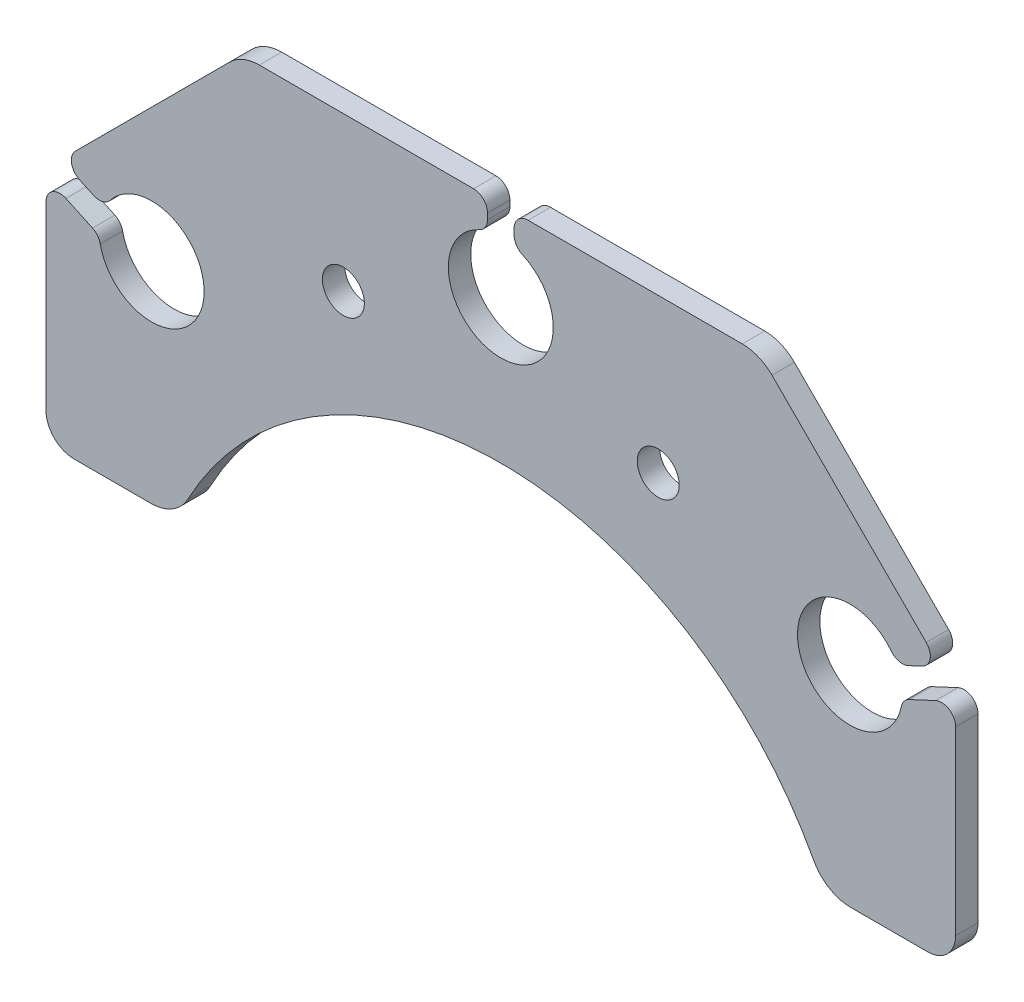
SolidWorks part; units mm, degrees
ref_plane "Ön Düzlem" through (0, 0, 0) normal (0, 0, 1) x (1, 0, 0)
ref_plane "Üst Düzlem" through (0, 0, 0) normal (0, 1, 0) x (1, 0, 0)
ref_plane "Sağ Düzlem" through (0, 0, 0) normal (1, 0, 0) x (0, 0, -1)
sketch "Çizim1" plane through (0, 0, 0) normal (0, 0, 1) x (1, 0, 0)
  line L0 (51.8787, -0.8787) -> (62.9014, -11.9014)
  line L1 (15.2426, 0) -> (30.55, 0)
  line L2 (0, -16.0697) -> (0, -29)
  line L3 (2, -31) -> (7.4942, -31)
  line L4 (65, -16.0697) -> (65, -29)
  line L5 (2.0986, -11.9014) -> (13.1213, -0.8787)
  line L6 (15.8302, -16) -> (49.1698, -16) construction
  line L7 (31.55, -1.4187) -> (31.55, -1)
  line L8 (33.45, -1.4187) -> (33.45, -1)
  line L9 (34.45, 0) -> (49.7574, 0)
  line L10 (57.5058, -31) -> (63, -31)
  line L11 (3.3844, -13.9818) -> (2.3831, -13.5148)
  line L12 (3.3194, -16.0479) -> (1.4226, -15.1634)
  line L13 (32.5, -41.343) -> (32.5, -25.2413) construction
  line L14 (61.6156, -13.9818) -> (62.6169, -13.5148)
  line L15 (61.6806, -16.0479) -> (63.5774, -15.1634)
  arc A0 (10.141, -29.4123) -> (54.859, -29.4123) centre (32.5, -41.343) cw
  arc A1 (30.9605, -2.3306) -> (34.0395, -2.3306) centre (32.5, -5.75) ccw
  arc A2 (3.8764, -16.7533) -> (4.595, -13.6912) centre (7.55, -16) ccw
  arc A3 (60.405, -13.6912) -> (61.1236, -16.7533) centre (57.45, -16) ccw
  circle A4 centre (21.25, -11) radius 1.5
  circle A5 centre (43.75, -11) radius 1.5
  arc A6 (33.45, -1.4187) -> (34.0395, -2.3306) centre (34.45, -1.4187) ccw
  arc A7 (31.55, -1.4187) -> (30.9605, -2.3306) centre (30.55, -1.4187) cw
  arc A8 (33.45, -1) -> (34.45, 0) centre (34.45, -1) cw
  arc A9 (31.55, -1) -> (30.55, 0) centre (30.55, -1) ccw
  arc A10 (61.6156, -13.9818) -> (60.405, -13.6912) centre (61.1929, -13.0755) cw
  arc A11 (61.6806, -16.0479) -> (61.1236, -16.7533) centre (62.1032, -16.9542) ccw
  arc A12 (63.5774, -15.1634) -> (65, -16.0697) centre (64, -16.0697) cw
  arc A13 (62.6169, -13.5148) -> (62.9014, -11.9014) centre (62.1943, -12.6085) ccw
  arc A14 (3.3844, -13.9818) -> (4.595, -13.6912) centre (3.8071, -13.0755) ccw
  arc A15 (3.3194, -16.0479) -> (3.8764, -16.7533) centre (2.8968, -16.9542) cw
  arc A16 (2.3831, -13.5148) -> (2.0986, -11.9014) centre (2.8057, -12.6085) cw
  arc A17 (1.4226, -15.1634) -> (0, -16.0697) centre (1, -16.0697) ccw
  arc A18 (51.8787, -0.8787) -> (49.7574, 0) centre (49.7574, -3) ccw
  arc A19 (13.1213, -0.8787) -> (15.2426, 0) centre (15.2426, -3) cw
  arc A20 (54.859, -29.4123) -> (57.5058, -31) centre (57.5058, -28) ccw
  arc A21 (10.141, -29.4123) -> (7.4942, -31) centre (7.4942, -28) cw
  arc A22 (63, -31) -> (65, -29) centre (63, -29) ccw
  arc A23 (0, -29) -> (2, -31) centre (2, -29) ccw
  point P0 (0, 0)
  point P3 (65, 0)
  point P37 (33.45, 0)
  point P42 (60.8191, -14.3532)
  point P45 (61.1898, -16.2767)
  point P50 (63.9113, -12.9113)
  point P53 (4.1809, -14.3532)
  point P57 (3.8102, -16.2767)
  point P60 (1.0887, -12.9113)
  point P63 (0, -14.5)
  point P66 (51, 0)
  point P69 (14, 0)
  point P72 (55.6363, -31)
  point P75 (9.3637, -31)
  point P80 (0, -31)
  dimension "D7" = 7.5
  dimension "D8" = 3
  dimension "D9" = 11
  dimension "D10" = 22.5
  dimension "D11" = 32.5
  dimension "D12" = 5.75
  dimension "D15" = 21.25
  dimension "D17" = 7.55
  dimension "D18" = 7.55
  dimension "D19" = 15
  dimension "D25" = 1
  dimension "D26" = 3
  dimension "D27" = 2
  dimension "D1" = 31
  dimension "D2" = 65
  dimension "D24" = 65
  dimension "D23" = 18.2593
  dimension "D3" = 46.2726
  dimension "D4" = 16
  dimension "D13" = 1.9
  dimension "D14" = 0.95
  dimension "D16" = 9.3637
  dimension "D20" = 1.9
  dimension "D21" = 65
  dimension "D22" = 16.5
extrude "Yükseklik-Ekstrüzyon1" add sketch "Çizim1" along normal blind 1.6
